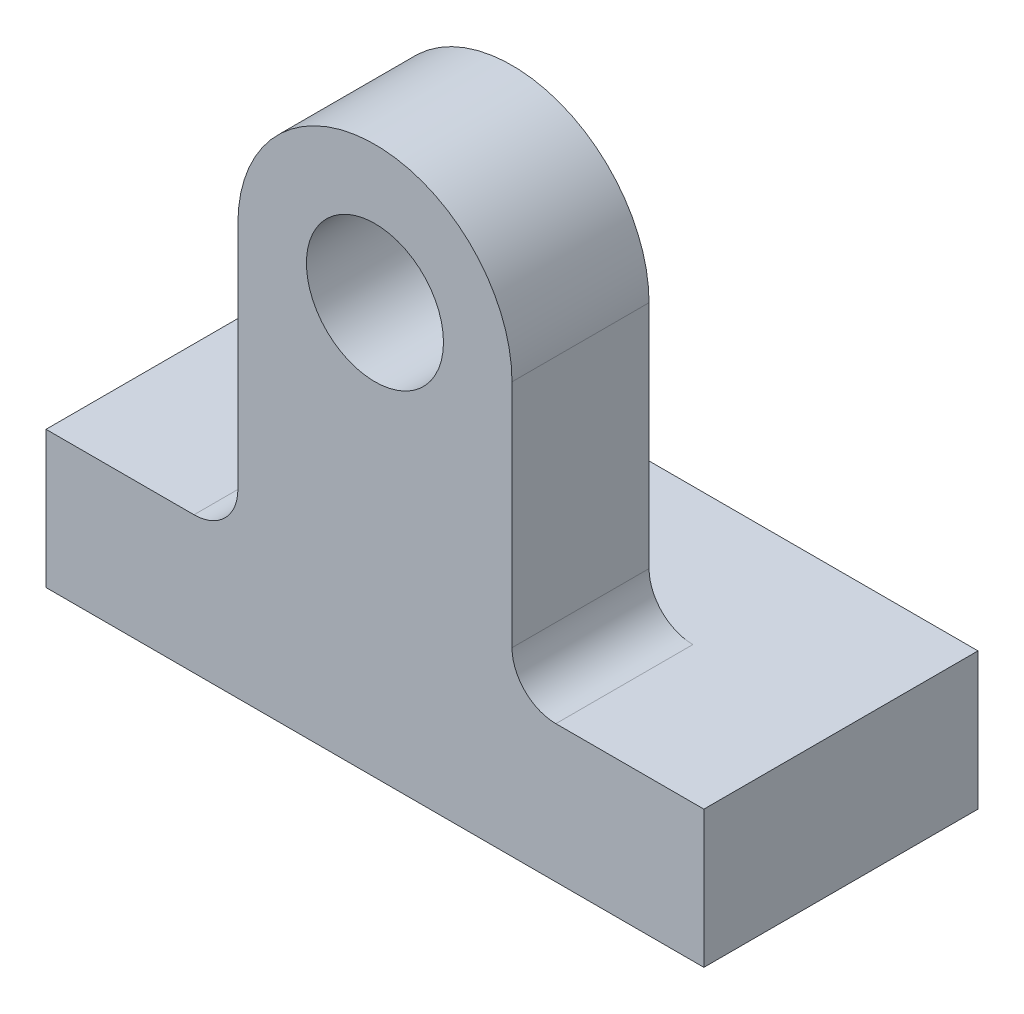
SolidWorks part; units mm, degrees
ref_plane "Front Plane" through (0, 0, 0) normal (0, 0, 1) x (1, 0, 0)
ref_plane "Top Plane" through (0, 0, 0) normal (0, 1, 0) x (1, 0, 0)
ref_plane "Right Plane" through (0, 0, 0) normal (1, 0, 0) x (0, 0, -1)
sketch "Sketch1" plane through (0, 0, 0) normal (0, 0, 1) x (1, 0, 0)
  line L0 (0, 45.957) -> (0, -25.2621) construction
  line L1 (-60, 0) -> (60, 0)
  line L2 (-60, 0) -> (-60, 25)
  line L3 (-60, 25) -> (60, 25)
  line L4 (60, 0) -> (60, 25)
  line L5 (-25, 25) -> (-25, 75)
  line L6 (25, 25) -> (25, 75)
  arc A0 (-25, 75) -> (25, 75) centre (0, 75) cw
  circle A1 centre (0, 75) radius 12.5
  point P0 (0, 0)
  point P8 (0, 0)
  dimension "D5" = 25
  dimension "D1" = 25
  dimension "D2" = 120
  dimension "D3" = 50
  dimension "D4" = 25
extrude "Boss-Extrude3" add sketch "Sketch1" along normal blind 50 contours L3 L0 L1 L4 | L0 L3 L2 L1
sketch "Sketch3" plane through (0, 0, 50) normal (0, 0, 1) x (1, 0, 0)
  line L0 (0, 57.7732) -> (0, -28.5222) construction
  line L1 (-25, 25) -> (-25, 75)
  line L2 (-60, 25) -> (60, 25) construction
  line L3 (25, 25) -> (25, 75)
  arc A0 (-25, 75) -> (25, 75) centre (0, 75) cw
  circle A1 centre (0, 75) radius 12.5
  dimension "D3" = 25
  dimension "D1" = 50
  dimension "D2" = 25
extrude "Boss-Extrude4" add sketch "Sketch3" against normal blind 25
fillet "Fillet1" radius 8 2 edges at (25, 25, 37.5) (-25, 25, 37.5)
